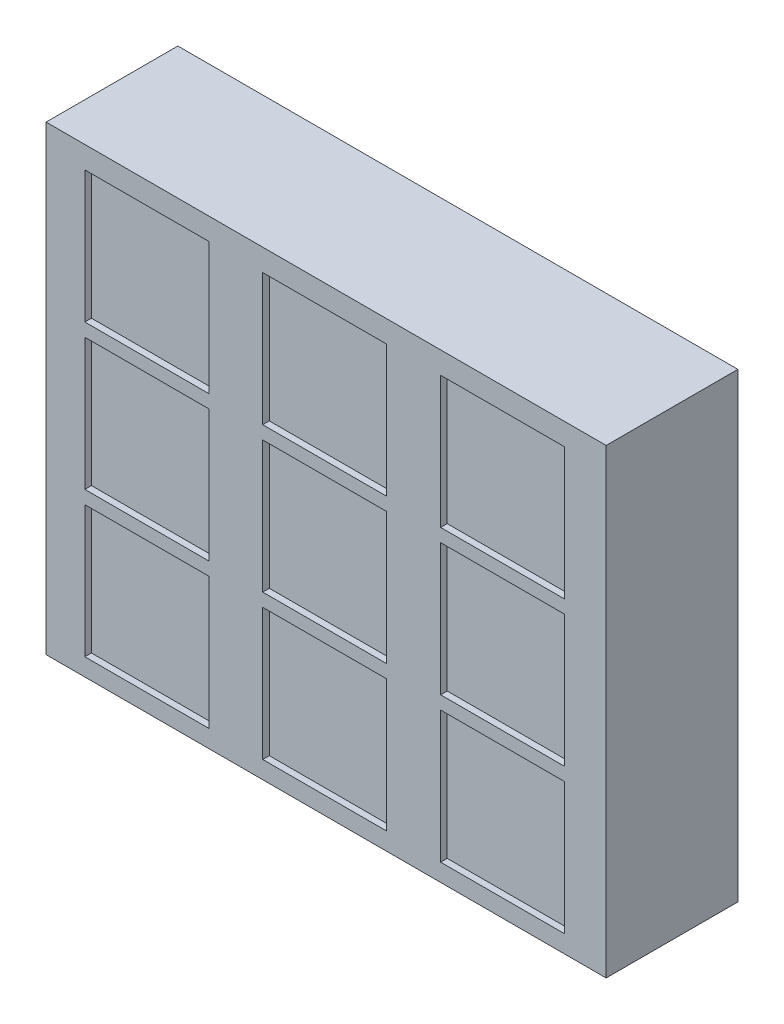
SolidWorks part; units mm, degrees
ref_plane "Front Plane" through (0, 0, 0) normal (0, 0, 1) x (1, 0, 0)
ref_plane "Top Plane" through (0, 0, 0) normal (0, 1, 0) x (1, 0, 0)
ref_plane "Right Plane" through (0, 0, 0) normal (1, 0, 0) x (0, 0, -1)
sketch "Sketch1" plane through (0, 0, 0) normal (0, 0, 1) x (1, 0, 0)
  line L1 (-107.95, -88.9) -> (107.95, -88.9)
  line L2 (-107.95, -88.9) -> (-107.95, 88.9)
  line L3 (-107.95, 88.9) -> (107.95, 88.9)
  line L4 (107.95, -88.9) -> (107.95, 88.9)
  line L5 (-107.95, -88.9) -> (107.95, 88.9) construction
  line L6 (-107.95, 88.9) -> (107.95, -88.9) construction
  point P0 (0, 0)
  dimension "D1" = 177.8
  dimension "D2" = 215.9
extrude "Boss-Extrude1" add sketch "Sketch1" along normal blind 50.8
sketch "Sketch2" plane through (0, 0, 50.8) normal (0, 0, 1) x (1, 0, 0)
  line L0 (-24.4392, 80.4229) -> (-24.4392, 29.6229)
  line L1 (-93.0192, 80.4229) -> (-45.2177, 80.4229)
  line L2 (-93.0192, 80.4229) -> (-93.0192, 29.6229)
  line L3 (-93.0192, 29.6229) -> (-45.2177, 29.6229)
  line L4 (-45.2177, 80.4229) -> (-45.2177, 29.6229)
  line L5 (-93.0192, 80.4229) -> (-45.2177, 29.6229) construction
  line L6 (-93.0192, 29.6229) -> (-45.2177, 80.4229) construction
  line L7 (-24.4392, 80.4229) -> (23.3623, 80.4229)
  line L8 (23.3623, 80.4229) -> (23.3623, 29.6229)
  line L9 (-24.4392, 29.6229) -> (23.3623, 29.6229)
  line L10 (44.1408, 80.4229) -> (44.1408, 29.6229)
  line L11 (44.1408, 80.4229) -> (91.9423, 80.4229)
  line L12 (91.9423, 80.4229) -> (91.9423, 29.6229)
  line L13 (44.1408, 29.6229) -> (91.9423, 29.6229)
  line L14 (-93.0192, 24.5429) -> (-93.0192, -26.2571)
  line L15 (-93.0192, 24.5429) -> (-45.2177, 24.5429)
  line L16 (-45.2177, 24.5429) -> (-45.2177, -26.2571)
  line L17 (-93.0192, -26.2571) -> (-45.2177, -26.2571)
  line L18 (-24.4392, 24.5429) -> (-24.4392, -26.2571)
  line L19 (-24.4392, -26.2571) -> (23.3623, -26.2571)
  line L20 (23.3623, 24.5429) -> (23.3623, -26.2571)
  line L21 (-24.4392, 24.5429) -> (23.3623, 24.5429)
  line L22 (44.1408, 24.5429) -> (44.1408, -26.2571)
  line L23 (44.1408, -26.2571) -> (91.9423, -26.2571)
  line L24 (91.9423, 24.5429) -> (91.9423, -26.2571)
  line L25 (44.1408, 24.5429) -> (91.9423, 24.5429)
  line L26 (-93.0192, -31.3371) -> (-93.0192, -82.1371)
  line L27 (-93.0192, -31.3371) -> (-45.2177, -31.3371)
  line L28 (-45.2177, -31.3371) -> (-45.2177, -82.1371)
  line L29 (-93.0192, -82.1371) -> (-45.2177, -82.1371)
  line L30 (-24.4392, -31.3371) -> (-24.4392, -82.1371)
  line L31 (-24.4392, -82.1371) -> (23.3623, -82.1371)
  line L32 (23.3623, -31.3371) -> (23.3623, -82.1371)
  line L33 (-24.4392, -31.3371) -> (23.3623, -31.3371)
  line L34 (44.1408, -31.3371) -> (44.1408, -82.1371)
  line L35 (44.1408, -82.1371) -> (91.9423, -82.1371)
  line L36 (91.9423, -31.3371) -> (91.9423, -82.1371)
  line L37 (44.1408, -31.3371) -> (91.9423, -31.3371)
  point P0 (-69.1185, 55.0229)
  dimension "D1" = 50.8
  dimension "D2" = 47.8015
  dimension "D3" = 3
  dimension "D4" = 3
extrude "Cut-Extrude1" cut sketch "Sketch2" against normal blind 2.54
sketch "Sketch3" plane through (0, 0, 0) normal (0, 0, -1) x (-1, 0, 0)
  line L1 (33.0751, 80.1821) -> (83.8751, 80.1821)
  line L2 (33.0751, 80.1821) -> (33.0751, 29.3821)
  line L3 (33.0751, 29.3821) -> (83.8751, 29.3821)
  line L4 (83.8751, 80.1821) -> (83.8751, 29.3821)
  line L5 (33.0751, 80.1821) -> (83.8751, 29.3821) construction
  line L6 (33.0751, 29.3821) -> (83.8751, 80.1821) construction
  line L7 (83.8751, -84.9179) -> (33.0751, -84.9179)
  line L8 (83.8751, -84.9179) -> (83.8751, -34.1179)
  line L9 (83.8751, -34.1179) -> (33.0751, -34.1179)
  line L10 (33.0751, -84.9179) -> (33.0751, -34.1179)
  line L11 (83.8751, -84.9179) -> (33.0751, -34.1179) construction
  line L12 (83.8751, -34.1179) -> (33.0751, -84.9179) construction
  line L17 (-55.8249, 29.3821) -> (-106.6249, 29.3821)
  line L18 (-55.8249, 29.3821) -> (-55.8249, -21.4179)
  line L19 (-55.8249, -21.4179) -> (-106.6249, -21.4179)
  line L20 (-106.6249, 29.3821) -> (-106.6249, -21.4179)
  point P0 (58.4751, 54.7821)
  point P5 (58.4751, -59.5179)
  point P11 (0, 0)
  point P12 (0, 0)
  dimension "D1" = 50.8
  dimension "D2" = 50.8
  dimension "D3" = 50.8
  dimension "D4" = 50.8
  dimension "D5" = 63.5
  dimension "D6" = 50.8
  dimension "D7" = 50.8
  dimension "D8" = 88.9
extrude "Cut-Extrude2" cut sketch "Sketch3" against normal blind 5.08
